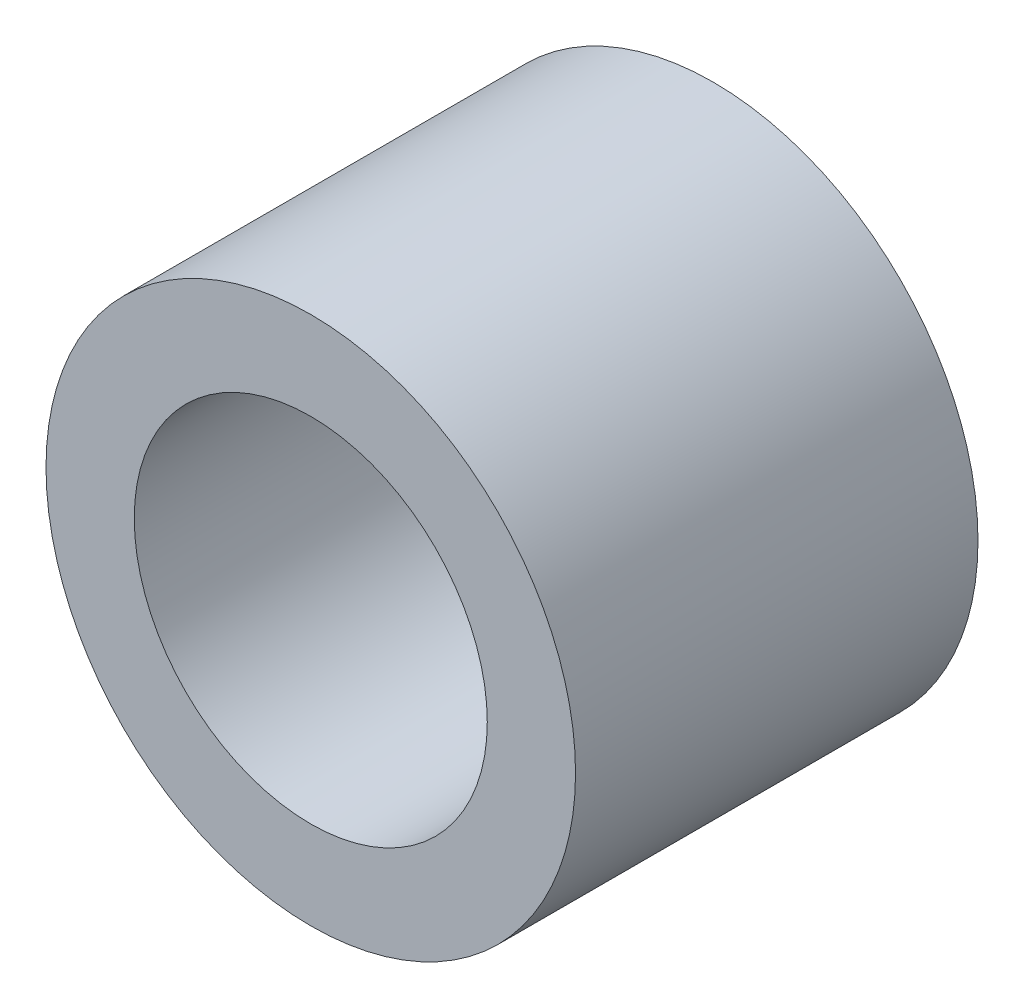
SolidWorks part; units mm, degrees
material "ABS"
ref_plane "Ebene vorne" through (0, 0, 0) normal (0, 0, 1) x (1, 0, 0)
ref_plane "Ebene oben" through (0, 0, 0) normal (0, 1, 0) x (1, 0, 0)
ref_plane "Ebene rechts" through (0, 0, 0) normal (1, 0, 0) x (0, 0, -1)
sketch "Skizze1" plane through (0, 0, 0) normal (0, 1, 0) x (1, 0, 0)
  circle A0 centre (0, 0) radius 7.5
  circle A1 centre (0, 0) radius 5
  dimension "D1" = 15
  dimension "D2" = 10
extrude "Aufsatz-Linear austragen1" add sketch "Skizze1" along normal blind 11.4
move or copy body "Körper-Verschieben/Kopieren1" bodies to move or copy 101 copy no rotation origin (0, 5.7, 0) rotation axis (-1, 0, 0) rotation angle 90
